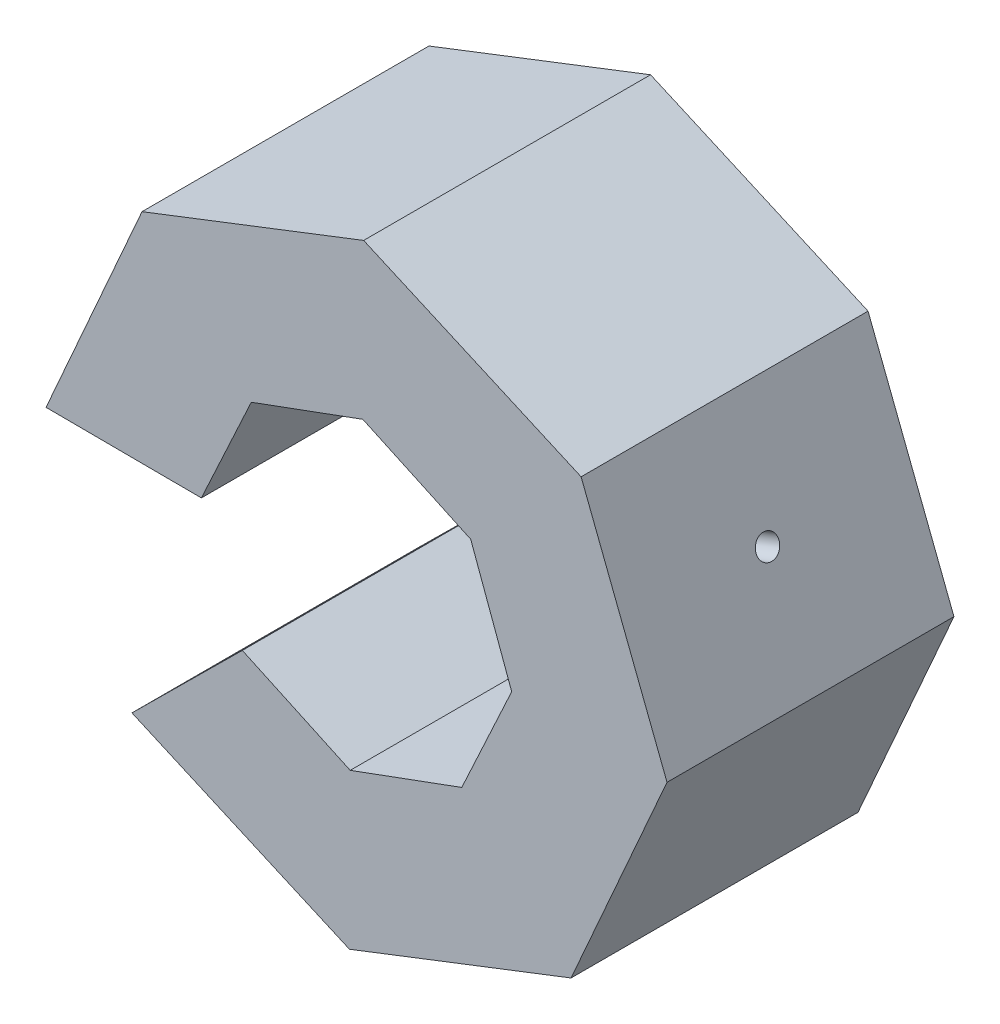
SolidWorks part; units mm, degrees
ref_plane "Front Plane" through (0, 0, 0) normal (0, 0, 1) x (1, 0, 0)
ref_plane "Top Plane" through (0, 0, 0) normal (0, 1, 0) x (1, 0, 0)
ref_plane "Right Plane" through (0, 0, 0) normal (1, 0, 0) x (0, 0, -1)
sketch "Sketch1" plane through (0, 0, 0) normal (0, 0, 1) x (1, 0, 0)
  line L0 (-10.8211, 0.2478) -> (-7.8269, -7.4764)
  line L1 (7.4764, -7.8269) -> (10.8211, -0.2478)
  line L2 (10.8211, -0.2478) -> (7.8269, 7.4764)
  line L3 (7.8269, 7.4764) -> (0.2478, 10.8211)
  line L4 (0.2478, 10.8211) -> (-7.4764, 7.8269)
  line L5 (-7.4764, 7.8269) -> (-10.8211, 0.2478)
  line L6 (-7.8269, -7.4764) -> (-0.2478, -10.8211)
  line L7 (-0.2478, -10.8211) -> (7.4764, -7.8269)
  line L8 (0, 0) -> (-9.324, -3.6143) construction
  line L9 (0, 0) -> (4.6935, 1.7237) construction
  line L10 (3.6678, -3.9795) -> (5.4075, -0.2204)
  line L11 (5.4075, -0.2204) -> (3.9795, 3.6678)
  line L12 (3.9795, 3.6678) -> (0.2204, 5.4075)
  line L13 (0.2204, 5.4075) -> (-3.6678, 3.9795)
  line L14 (-3.6678, 3.9795) -> (-5.4075, 0.2204)
  line L15 (-5.4075, 0.2204) -> (-3.9795, -3.6678)
  line L16 (-3.9795, -3.6678) -> (-0.2204, -5.4075)
  line L17 (-0.2204, -5.4075) -> (3.6678, -3.9795)
  line L18 (-5.4075, 0.2204) -> (-10.8211, 0.2478)
  line L19 (-3.9795, -3.6678) -> (-7.8269, -7.4764)
  circle A0 centre (0, 0) radius 10 construction
  circle A1 centre (0, 0) radius 5 construction
  dimension "D1" = 10
  dimension "D2" = 5
extrude "Boss-Extrude1" add sketch "Sketch1" against normal blind 10 contours L16 L19 L6 L7 L1 L2 L3 L4 L5 L18 L14 L13 L12 L11 L10 L17
sketch "Sketch2" plane through (9.324, 3.6143, 0) normal (0.9324, 0.3614, 0) x (0, 0, -1)
  line L0 (0, 4.1421) -> (10, -4.1421) construction
  line L1 (5, 0) -> (5.3976, -0.0439) construction
  circle A0 centre (5, 0) radius 0.4
  dimension "D1" = 0.4
extrude "Cut-Extrude1" cut sketch "Sketch2" against normal blind 602
ref_plane "Plane2" through (-7.4764, 7.8269, -10) normal (-0.9324, -0.3614, 0) x (0, 0, 1)
